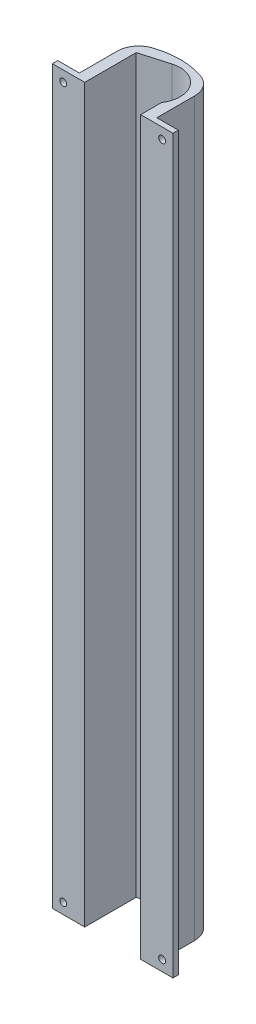
SolidWorks part; units mm, degrees
ref_plane "Front Plane" through (0, 0, 0) normal (0, 0, 1) x (1, 0, 0)
ref_plane "Top Plane" through (0, 0, 0) normal (0, 1, 0) x (1, 0, 0)
ref_plane "Right Plane" through (0, 0, 0) normal (1, 0, 0) x (0, 0, -1)
sketch "Sketch1" plane through (0, 0, 0) normal (0, 1, 0) x (1, 0, 0)
  line L0 (-20.574, -9.6521) -> (-4.162, -14.3967) construction
  line L1 (-4.1621, 14.3967) -> (-20.574, 9.652) construction
  line L2 (-20.574, 9.652) -> (-20.574, -9.6521) construction
  line L3 (-39.624, 20.7467) -> (-20.574, 20.7467) construction
  line L4 (-39.624, 20.7467) -> (-39.624, 17.5717) construction
  line L6 (12.446, 20.7467) -> (31.496, 20.7467) construction
  line L7 (-39.624, 17.5717) -> (-26.924, 17.5717) construction
  line L9 (-26.924, 17.5717) -> (-26.924, -12.8271) construction
  line L10 (31.496, 20.7467) -> (31.496, 17.5717) construction
  line L11 (31.496, 17.5717) -> (18.796, 17.5717) construction
  line L12 (18.796, 17.5717) -> (18.796, -12.8271) construction
  line L13 (-20.574, 9.652) -> (-20.574, 20.7467) construction
  line L14 (12.446, 20.7467) -> (12.446, 8.3478) construction
  line L15 (-69.4628, -37.4601) -> (67.1627, -37.4601) construction
  line L16 (-4.1621, -89.3169) -> (-20.574, -84.5722) construction
  line L17 (12.446, -95.6669) -> (12.446, -83.268)
  line L18 (-20.574, -84.5722) -> (-20.574, -95.6669)
  line L19 (18.796, -92.4919) -> (18.796, -62.0931)
  line L20 (31.496, -92.4919) -> (18.796, -92.4919)
  line L21 (31.496, -95.6669) -> (31.496, -92.4919)
  line L22 (-26.924, -92.4919) -> (-26.924, -62.0931)
  line L23 (-39.624, -92.4919) -> (-26.924, -92.4919)
  line L24 (12.446, -95.6669) -> (31.496, -95.6669)
  line L25 (-39.624, -95.6669) -> (-39.624, -92.4919)
  line L26 (-39.624, -95.6669) -> (-20.574, -95.6669)
  line L27 (-20.574, -84.5722) -> (-20.574, -65.2681)
  line L28 (-20.574, -65.2681) -> (-4.162, -60.5234)
  arc A0 (-4.162, -14.3967) -> (12.446, 8.3478) centre (0, 0) ccw construction
  arc A1 (-26.924, -12.8271) -> (18.796, -12.8271) centre (-4.064, 25.294) ccw construction
  arc A2 (12.446, 8.3478) -> (-4.1621, 14.3967) centre (0, 0) ccw construction
  arc A3 (12.446, -83.268) -> (-4.1621, -89.3169) centre (0, -74.9202) cw construction
  arc A4 (-26.924, -62.0931) -> (18.796, -62.0931) centre (-4.064, -100.2142) cw
  arc A5 (-4.162, -60.5234) -> (12.446, -83.268) centre (0, -74.9202) cw
  point P6 (12.446, 14.5473)
  dimension "D2" = 14.9863
  dimension "D14" = 37.4601
  dimension "D10" = 44.45
  dimension "D1" = 19.3041
  dimension "D3" = 16.4119
  dimension "D4" = 106.124
  dimension "D5" = 20.574
  dimension "D6" = 106.125
  dimension "D7" = 6.35
  dimension "D8" = 6.35
  dimension "D9" = 3.175
  dimension "D11" = 12.7
  dimension "D12" = 3.175
  dimension "D13" = 33.02
  dimension "D15" = 6.35
extrude "Boss-Extrude1" add sketch "Sketch1" along normal blind 431.8
fillet "Fillet2" radius 12.7 2 edges at (18.796, 215.9, 62.0931) (-26.924, 215.9, 62.0931)
sketch "Sketch2" plane through (0, 0, 92.4919) normal (0, 0, -1) x (-1, 0, 0)
  line L0 (-31.496, 0) -> (-18.796, 0) construction
  line L2 (39.624, 431.8) -> (39.624, 0) construction
  line L3 (-31.496, 431.8) -> (-18.796, 431.8) construction
  circle A0 centre (-25.146, 425.45) radius 2.032
  circle A1 centre (-25.146, 6.35) radius 2.032
  circle A2 centre (33.274, 425.45) radius 2.032
  circle A3 centre (33.274, 6.35) radius 2.032
  dimension "D1" = 4.064
  dimension "D2" = 6.35
  dimension "D3" = 6.35
  dimension "D4" = 6.35
  dimension "D5" = 6.35
extrude "Cut-Extrude1" cut sketch "Sketch2" against normal through all
scale "Scale1" scale about centroid uniform scaling yes scale factor 0.25
